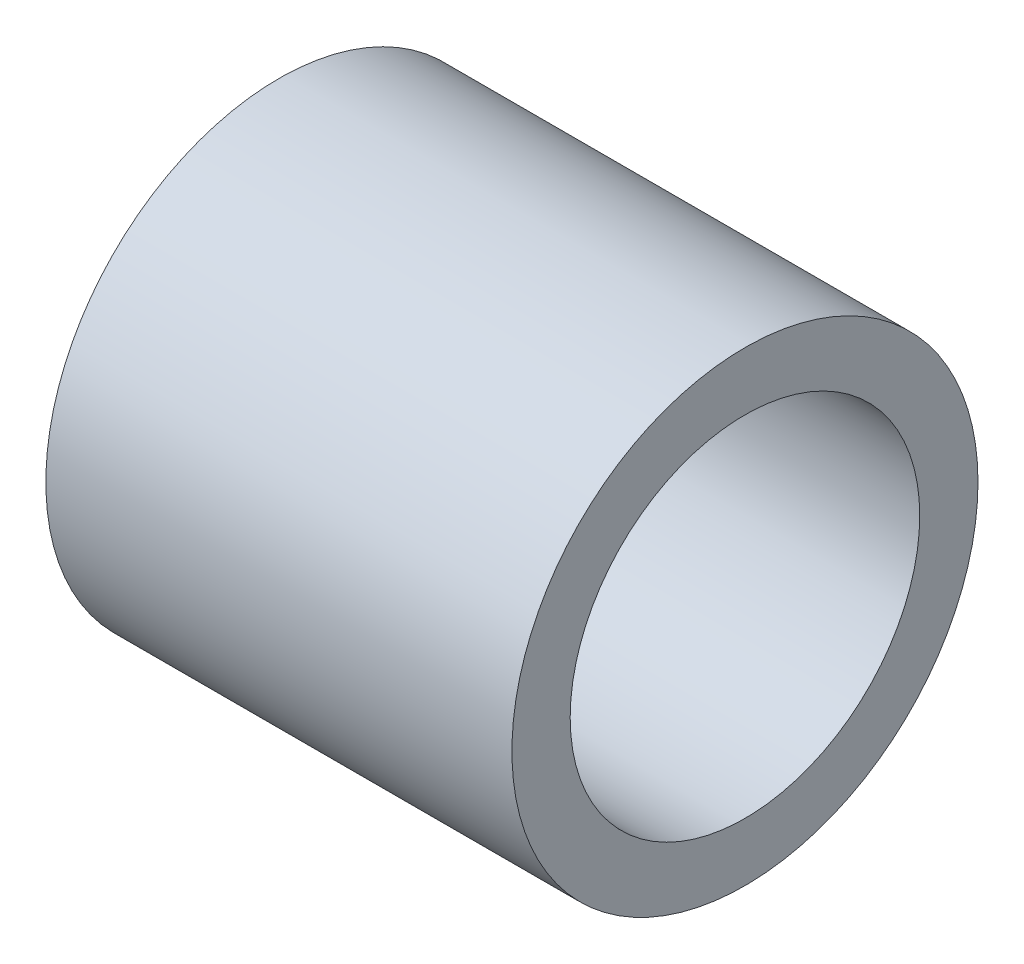
SolidWorks part; units mm, degrees
ref_plane "Front Plane" through (0, 0, 0) normal (0, 0, 1) x (1, 0, 0)
ref_plane "Top Plane" through (0, 0, 0) normal (0, 1, 0) x (1, 0, 0)
ref_plane "Right Plane" through (0, 0, 0) normal (1, 0, 0) x (0, 0, -1)
sketch "Sketch1" plane through (0, 0, 0) normal (1, 0, 0) x (0, 0, -1)
  circle A0 centre (0, 0) radius 12.7
  circle A1 centre (0, 0) radius 9.525
  dimension "D1" = 25.4
  dimension "D2" = 19.05
extrude "Boss-Extrude1" add sketch "Sketch1" along normal mid plane 25.4
